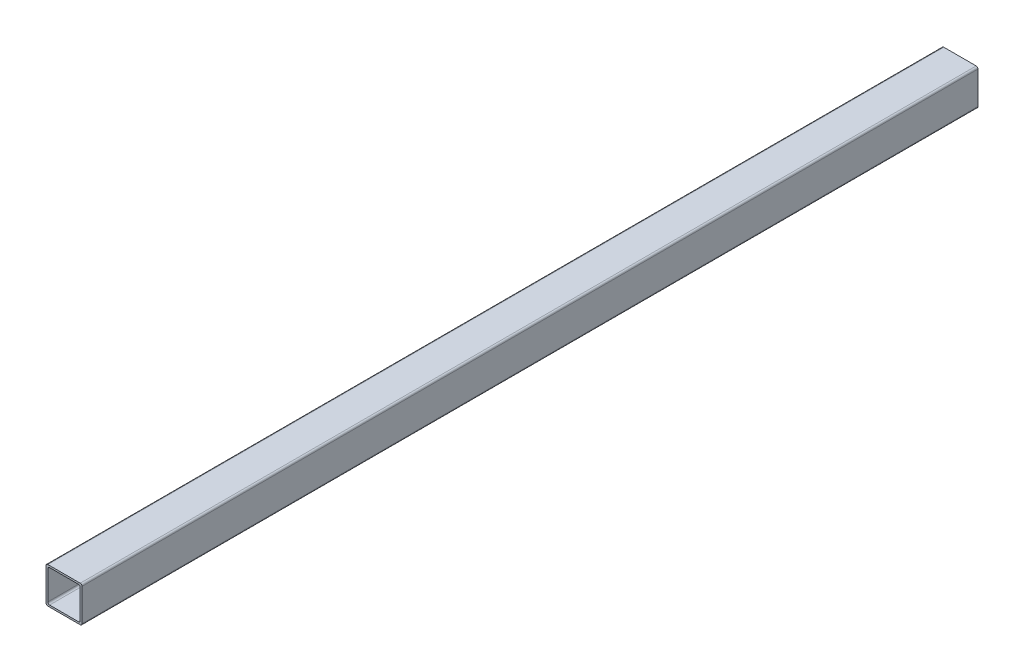
SolidWorks part; units mm, degrees
ref_plane "Спереди" through (0, 0, 0) normal (0, 0, 1) x (1, 0, 0)
ref_plane "Сверху" through (0, 0, 0) normal (0, 1, 0) x (1, 0, 0)
ref_plane "Справа" through (0, 0, 0) normal (1, 0, 0) x (0, 0, -1)
sketch "Эскиз1" plane through (0, 0, 0) normal (0, 0, 1) x (1, 0, 0)
  line L1 (-18, 20) -> (18, 20)
  line L2 (-20, 18) -> (-20, -18)
  line L3 (-18, -20) -> (18, -20)
  line L4 (20, 18) -> (20, -18)
  line L5 (-20, 20) -> (20, -20) construction
  line L6 (-20, -20) -> (20, 20) construction
  line L7 (16, -18) -> (-16, -18)
  line L8 (18, -16) -> (18, 16)
  line L9 (16, 18) -> (-16, 18)
  line L10 (-18, -16) -> (-18, 16)
  line L11 (18, -18) -> (-18, 18) construction
  line L12 (18, 18) -> (-18, -18) construction
  arc A0 (18, 16) -> (16, 18) centre (16, 16) ccw
  arc A1 (18, 20) -> (20, 18) centre (18, 18) cw
  arc A2 (18, -20) -> (20, -18) centre (18, -18) ccw
  arc A3 (16, -18) -> (18, -16) centre (16, -16) ccw
  arc A4 (-16, -18) -> (-18, -16) centre (-16, -16) cw
  arc A5 (-20, -18) -> (-18, -20) centre (-18, -18) ccw
  arc A6 (-18, 20) -> (-20, 18) centre (-18, 18) ccw
  arc A7 (-16, 18) -> (-18, 16) centre (-16, 16) ccw
  point P0 (0, 0)
  point P6 (0, 0)
  dimension "D5" = 2
  dimension "D1" = 40
  dimension "D2" = 40
  dimension "D3" = 2
  dimension "D4" = 2
extrude "Бобышка-Вытянуть1" add sketch "Эскиз1" along normal blind 995
